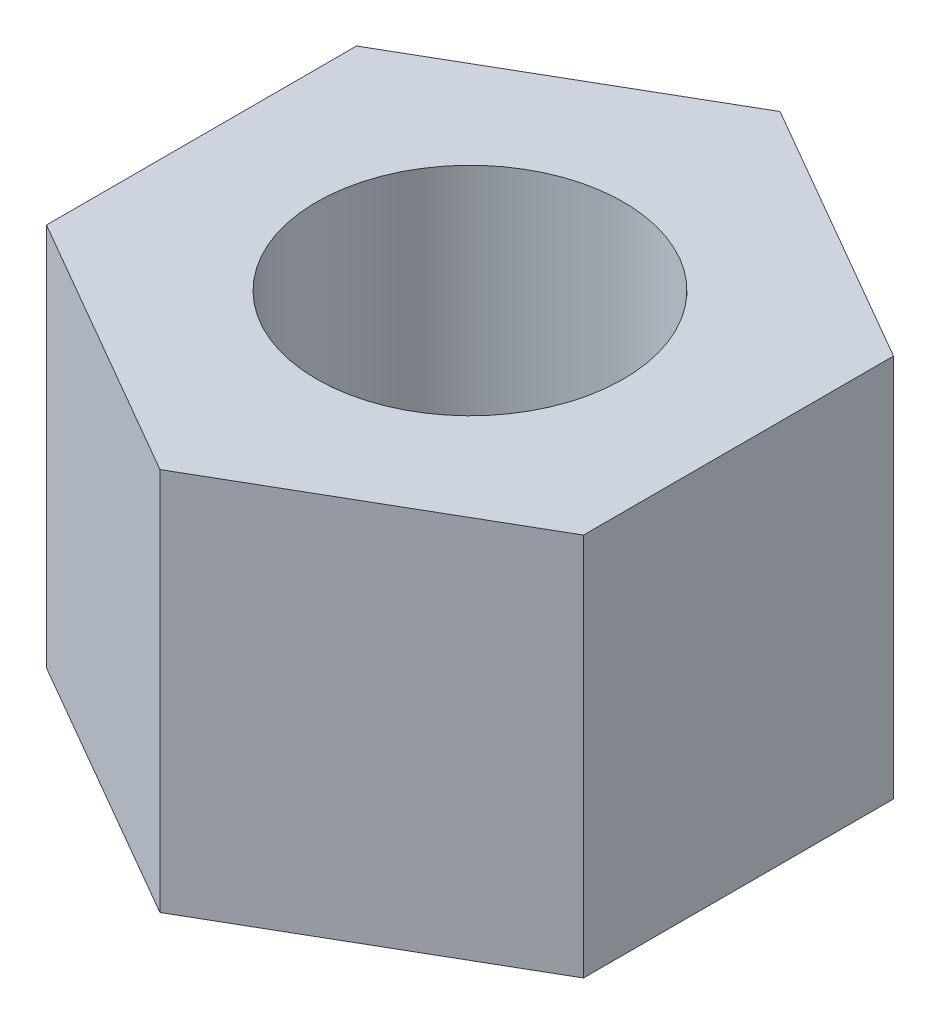
SolidWorks part; units mm, degrees
material "AISI 304"
ref_plane "前视基准面" through (0, 0, 0) normal (0, 0, 1) x (1, 0, 0)
ref_plane "上视基准面" through (0, 0, 0) normal (0, 1, 0) x (1, 0, 0)
ref_plane "右视基准面" through (0, 0, 0) normal (1, 0, 0) x (0, 0, -1)
other "Configuration Table"
sketch "草图1" plane through (0, 0, 0) normal (0, 1, 0) x (1, 0, 0)
  line L1 (0, 4.0415) -> (-3.5, 2.0207)
  line L2 (-3.5, 2.0207) -> (-3.5, -2.0207)
  line L3 (-3.5, -2.0207) -> (0, -4.0415)
  line L4 (0, -4.0415) -> (3.5, -2.0207)
  line L5 (3.5, -2.0207) -> (3.5, 2.0207)
  line L6 (3.5, 2.0207) -> (0, 4.0415)
  circle A0 centre (0, 0) radius 2
  circle A1 centre (0, 0) radius 3.5 construction
  dimension "D1" = 4
  dimension "D2" = 7
extrude "凸台-拉伸1" add sketch "草图1" along normal blind 5
